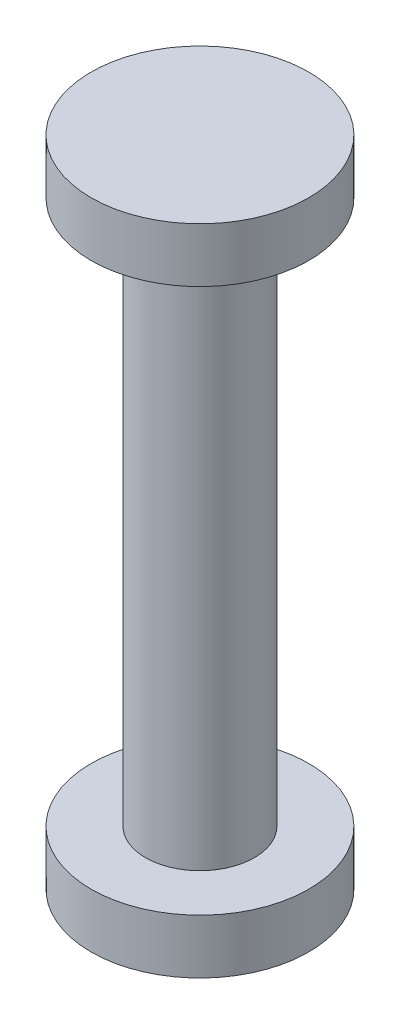
SolidWorks part; units mm, degrees
ref_plane "Front Plane" through (0, 0, 0) normal (0, 0, 1) x (1, 0, 0)
ref_plane "Top Plane" through (0, 0, 0) normal (0, 1, 0) x (1, 0, 0)
ref_plane "Right Plane" through (0, 0, 0) normal (1, 0, 0) x (0, 0, -1)
sketch "Sketch1" plane through (0, 0, 0) normal (0, 1, 0) x (1, 0, 0)
  circle A0 centre (0, 0) radius 5
  dimension "D1" = 10
extrude "Boss-Extrude1" add sketch "Sketch1" along normal mid plane 50
sketch "Sketch2" plane through (0, 25, 0) normal (0, 1, 0) x (1, 0, 0)
  circle A0 centre (0, 0) radius 10
  dimension "D1" = 20
extrude "Boss-Extrude2" add sketch "Sketch2" along normal blind 5
mirror "Mirror2" about plane through (0, 0, 0) normal (0, 1, 0) of "Boss-Extrude2"
